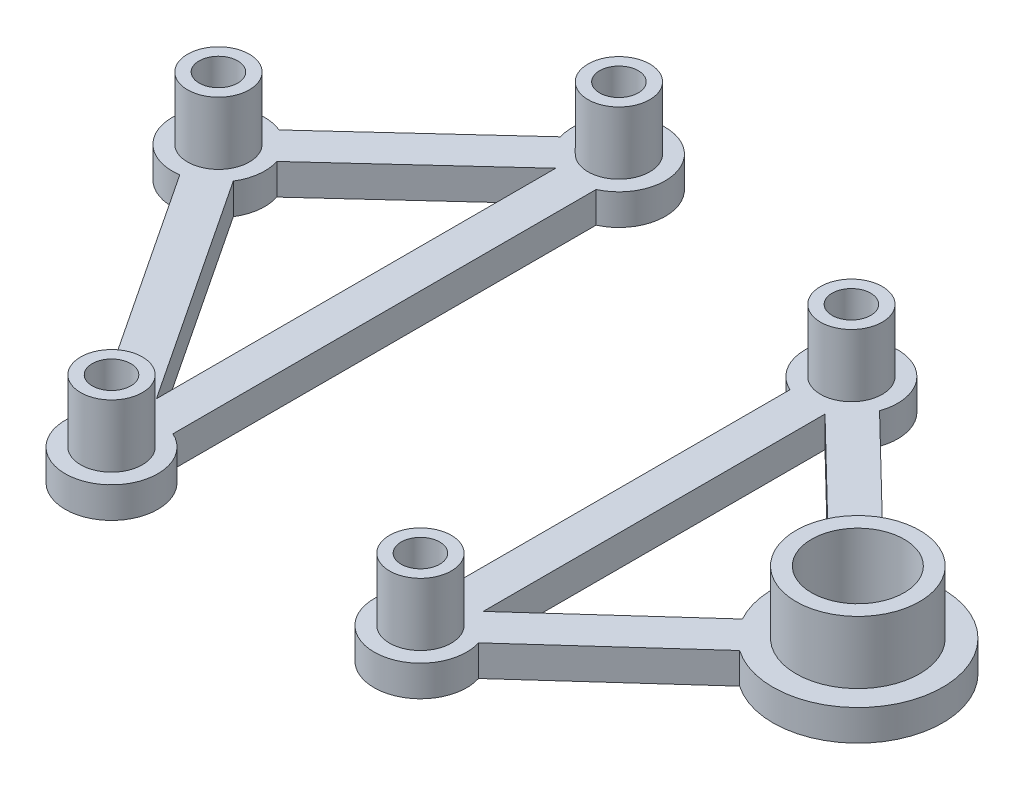
SolidWorks part; units mm, degrees
ref_plane "Спереди" through (0, 0, 0) normal (0, 0, 1) x (1, 0, 0)
ref_plane "Сверху" through (0, 0, 0) normal (0, 1, 0) x (1, 0, 0)
ref_plane "Справа" through (0, 0, 0) normal (1, 0, 0) x (0, 0, -1)
other "Configuration Table"
sketch "Эскиз1" plane through (0, 0, 0) normal (0, 1, 0) x (1, 0, 0)
  line L0 (-67.0272, 40.8721) -> (-40, 0) construction
  line L1 (-40, 0) -> (-40, 65.7) construction
  line L2 (-40, 65.7) -> (-67.0272, 40.8721) construction
  line L3 (0, 55.8) -> (29.7602, 26.8763) construction
  line L4 (29.7602, 26.8763) -> (0, 0) construction
  line L5 (0, 55.8) -> (0, 0) construction
  line L6 (0, 0) -> (-40, 0) construction
  line L8 (-66.0981, 34.9348) -> (-43.8076, 1.2257) construction
  line L11 (-48.2821, 17.0572) -> (-25.9916, -16.6519) construction
  line L12 (-37.5, 40.8721) -> (-37.5, 25.5534) construction
  line L14 (-42.5, 45.1596) -> (-42.5, 29.8408) construction
  line L15 (-58.9446, 51.6917) -> (-52.0529, 58.0226) construction
  line L17 (-54.6234, 48.8719) -> (-47.7317, 55.2027) construction
  line L18 (-64.7017, 46.4032) -> (-45.708, 63.8512)
  line L20 (-37.5, 60.2456) -> (-37.5, 5.4544)
  line L22 (-66.104, 34.9436) -> (-45.0938, 3.1707)
  line L32 (-61.3191, 42.721) -> (-42.5, 60.0087)
  line L33 (-42.5, 60.0087) -> (-42.5, 8.3131)
  line L34 (-42.5, 8.3131) -> (-61.9334, 37.7015)
  line L36 (-2.5, 38.1926) -> (-2.5, 20.958) construction
  line L38 (2.5, 19.403) -> (2.5, 2.1683) construction
  line L39 (9.5911, 49.9647) -> (19.4126, 40.4193) construction
  line L41 (9.1257, 43.4447) -> (18.1439, 34.68) construction
  line L43 (9.8251, 12.2416) -> (16.8272, 18.5652) construction
  line L45 (11.5829, 7.0919) -> (19.8959, 14.5993) construction
  line L46 (20.1346, 21.5521) -> (2.5, 5.6263)
  line L53 (2.5, 5.6263) -> (2.5, 49.8841)
  line L55 (2.5, 49.8841) -> (20.336, 32.5494)
  line L57 (-2.5, 50.3456) -> (-2.5, 5.4544)
  line L58 (5.7235, 1.8003) -> (23.4858, 17.8413)
  line L59 (5.6538, 53.7913) -> (23.8208, 36.135)
  circle A14 centre (-40, 65.7) radius 6 construction
  circle A15 centre (-67.0272, 40.8721) radius 6 construction
  circle A16 centre (-40, 0) radius 6 construction
  circle A17 centre (0, 0) radius 6 construction
  circle A18 centre (29.7602, 26.8763) radius 11 construction
  circle A19 centre (0, 55.8) radius 6 construction
  arc A20 (-66.104, 34.9436) -> (-64.7017, 46.4032) centre (-67.0272, 40.8721) cw
  arc A21 (-45.708, 63.8512) -> (-37.5, 60.2456) centre (-40, 65.7) cw
  arc A22 (-45.0938, 3.1707) -> (-37.5, 5.4544) centre (-40, 0) ccw
  arc A23 (-61.3191, 42.721) -> (-61.9334, 37.7015) centre (-67.0272, 40.8721) cw
  arc A24 (5.6538, 53.7913) -> (-2.5, 50.3456) centre (0, 55.8) ccw
  arc A25 (23.4858, 17.8413) -> (23.8208, 36.135) centre (29.7602, 26.8763) ccw
  arc A26 (-2.5, 5.4544) -> (5.7235, 1.8003) centre (0, 0) ccw
  arc A27 (20.336, 32.5494) -> (20.1346, 21.5521) centre (29.7602, 26.8763) ccw
  dimension "D14" = 12
  dimension "D15" = 12
  dimension "D16" = 12
  dimension "D17" = 12
  dimension "D18" = 12
  dimension "D19" = 22
  dimension "D1" = 55.8
  dimension "D2" = 40.1
  dimension "D3" = 41.5
  dimension "D4" = 65.7
  dimension "D5" = 49
  dimension "D6" = 36.7
  dimension "D7" = 40
  dimension "D8" = 2.5
  dimension "D9" = 2.5
  dimension "D10" = 2.5
  dimension "D11" = 2.5
  dimension "D12" = 2.5
  dimension "D13" = 2.5
  dimension "D20" = 2.5
  dimension "D21" = 2.5
  dimension "D22" = 2.5
  dimension "D23" = 2.5
  dimension "D24" = 2.5
  dimension "D25" = 2.5
extrude "Бобышка-Вытянуть1" add sketch "Эскиз1" along normal blind 4
sketch "Эскиз3" plane through (0, 4, 0) normal (0, 1, 0) x (1, 0, 0)
  circle A1 centre (-67.0272, 40.8721) radius 4
  circle A2 centre (-40, 65.7) radius 4
  circle A4 centre (-40, 0) radius 4
  circle A6 centre (-67.0272, 40.8721) radius 2.5
  circle A7 centre (-40, 65.7) radius 2.5
  circle A8 centre (-40, 0) radius 2.5
  dimension "D1" = 8
  dimension "D3" = 8
  dimension "D6" = 8
  dimension "D2" = 5
  dimension "D4" = 5
  dimension "D5" = 5
extrude "Бобышка-Вытянуть2" add sketch "Эскиз3" along normal blind 8.1
sketch "Эскиз5" plane through (0, 4, 0) normal (0, 1, 0) x (1, 0, 0)
  circle A0 centre (0, 55.8) radius 4
  circle A2 centre (0, 0) radius 4
  circle A4 centre (29.7602, 26.8763) radius 8
  circle A6 centre (0, 55.8) radius 2.5
  circle A7 centre (0, 0) radius 2.5
  dimension "D1" = 8
  dimension "D4" = 5
  dimension "D5" = 5
  dimension "D2" = 8
  dimension "D3" = 16
extrude "Бобышка-Вытянуть3" add sketch "Эскиз5" along normal blind 8.1
sketch "Эскиз6" plane through (0, 12.1, 0) normal (0, 1, 0) x (1, 0, 0)
  circle A4 centre (29.7602, 26.8763) radius 6
  dimension "D1" = 12
extrude "Вырез-Вытянуть1" cut sketch "Эскиз6" against normal through all
equation "\"A\"= 12мм"
equation "\"B\"= 22мм"
equation "\"w\"= 5мм"
equation "\"D8@Эскиз1\"=\"w\"/2"
equation "\"D9@Эскиз1\"=\"w\"/2"
equation "\"D10@Эскиз1\"=\"w\"/2"
equation "\"D11@Эскиз1\"=\"w\"/2"
equation "\"D12@Эскиз1\"=\"w\"/2"
equation "\"D13@Эскиз1\"=\"w\"/2"
equation "\"D14@Эскиз1\"=\"A\""
equation "\"D15@Эскиз1\"=\"A\""
equation "\"D16@Эскиз1\"=\"A\""
equation "\"D17@Эскиз1\"=\"A\""
equation "\"D18@Эскиз1\"=\"A\""
equation "\"D19@Эскиз1\"=\"B\""
equation "\"D20@Эскиз1\"=\"w\"/2"
equation "\"D21@Эскиз1\"=\"w\"/2"
equation "\"D22@Эскиз1\"=\"w\"/2"
equation "\"D23@Эскиз1\"=\"w\"/2"
equation "\"D24@Эскиз1\"=\"w\"/2"
equation "\"D25@Эскиз1\"=\"w\"/2"
equation "\"innd\"= 5мм"
equation "\"extd\"= 8мм"
equation "\"D1@Эскиз3\"=\"extd\""
equation "\"D3@Эскиз3\"=\"extd\""
equation "\"D6@Эскиз3\"=\"extd\""
equation "\"D1@Эскиз5\"=\"extd\""
equation "\"D2@Эскиз5\"=\"extd\""
equation "\"D2@Эскиз3\"=\"innd\""
equation "\"D4@Эскиз3\"=\"innd\""
equation "\"D5@Эскиз3\"=\"innd\""
equation "\"D4@Эскиз5\"=\"innd\""
equation "\"D5@Эскиз5\"=\"innd\""
